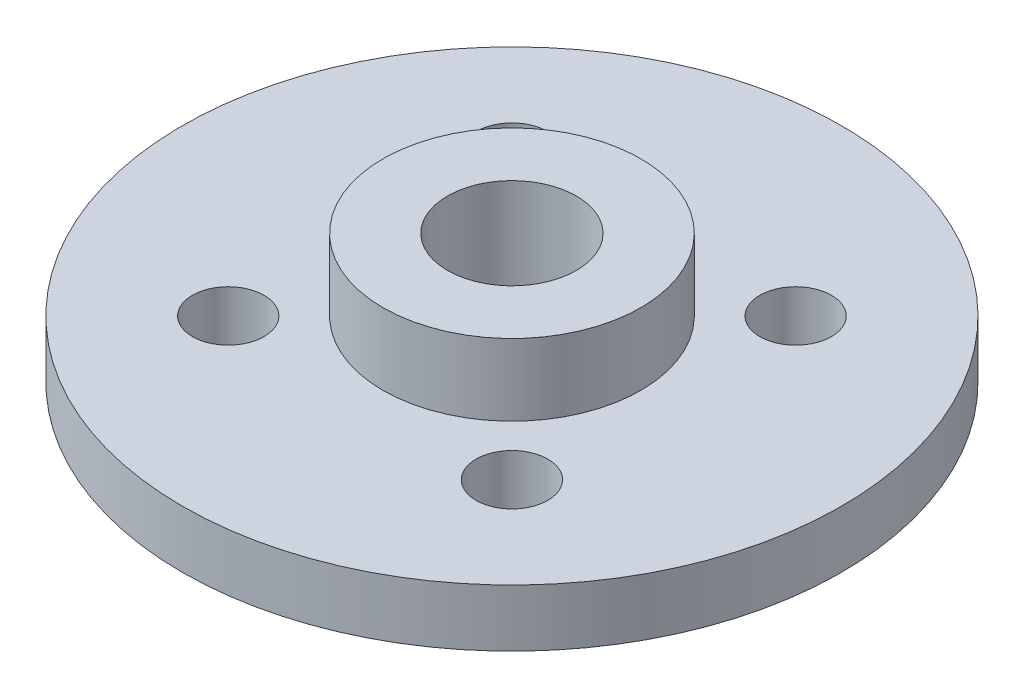
SolidWorks part; units mm, degrees
ref_plane "Front Plane" through (0, 0, 0) normal (0, 0, 1) x (1, 0, 0)
ref_plane "Top Plane" through (0, 0, 0) normal (0, 1, 0) x (1, 0, 0)
ref_plane "Right Plane" through (0, 0, 0) normal (1, 0, 0) x (0, 0, -1)
sketch "Sketch1" plane through (0, 0, 0) normal (0, 1, 0) x (1, 0, 0)
  line L0 (-4.9497, 4.9497) -> (4.9497, 4.9497) construction
  line L1 (4.9497, 4.9497) -> (4.9497, -4.9497) construction
  circle A0 centre (0, 0) radius 11.5
  circle A1 centre (-4.9497, 4.9497) radius 1.25
  circle A2 centre (4.9497, 4.9497) radius 1.25
  circle A3 centre (4.9497, -4.9497) radius 1.25
  circle A4 centre (-4.9497, -4.9497) radius 1.25
  circle A5 centre (0, 0) radius 7 construction
  circle A6 centre (0, 0) radius 1.5
  dimension "D1" = 23
  dimension "D2" = 2.5
  dimension "D3" = 3
  dimension "D4" = 14
extrude "Boss-Extrude1" add sketch "Sketch1" along normal blind 2
cosmetic thread "Cosmetic Thread1" parameters "D2"=3
cosmetic thread "Cosmetic Thread2" parameters "D2"=3
cosmetic thread "Cosmetic Thread3" parameters "D2"=3
cosmetic thread "Cosmetic Thread4" parameters "D2"=3
sketch "Sketch2" plane through (0, 2, 0) normal (0, 1, 0) x (1, 0, 0)
  circle A0 centre (0, 0) radius 4.5
  circle A1 centre (0, 0) radius 1.5 construction
  circle A2 centre (0, 0) radius 1.5
  dimension "D1" = 9
extrude "Boss-Extrude2" add sketch "Sketch2" along normal blind 2.5
sketch "Sketch3" plane through (0, 4.5, 0) normal (0, 1, 0) x (1, 0, 0)
  circle A0 centre (0, 0) radius 2.25
  dimension "D1" = 4.5
extrude "Cut-Extrude1" cut sketch "Sketch3" against normal blind 3.6
